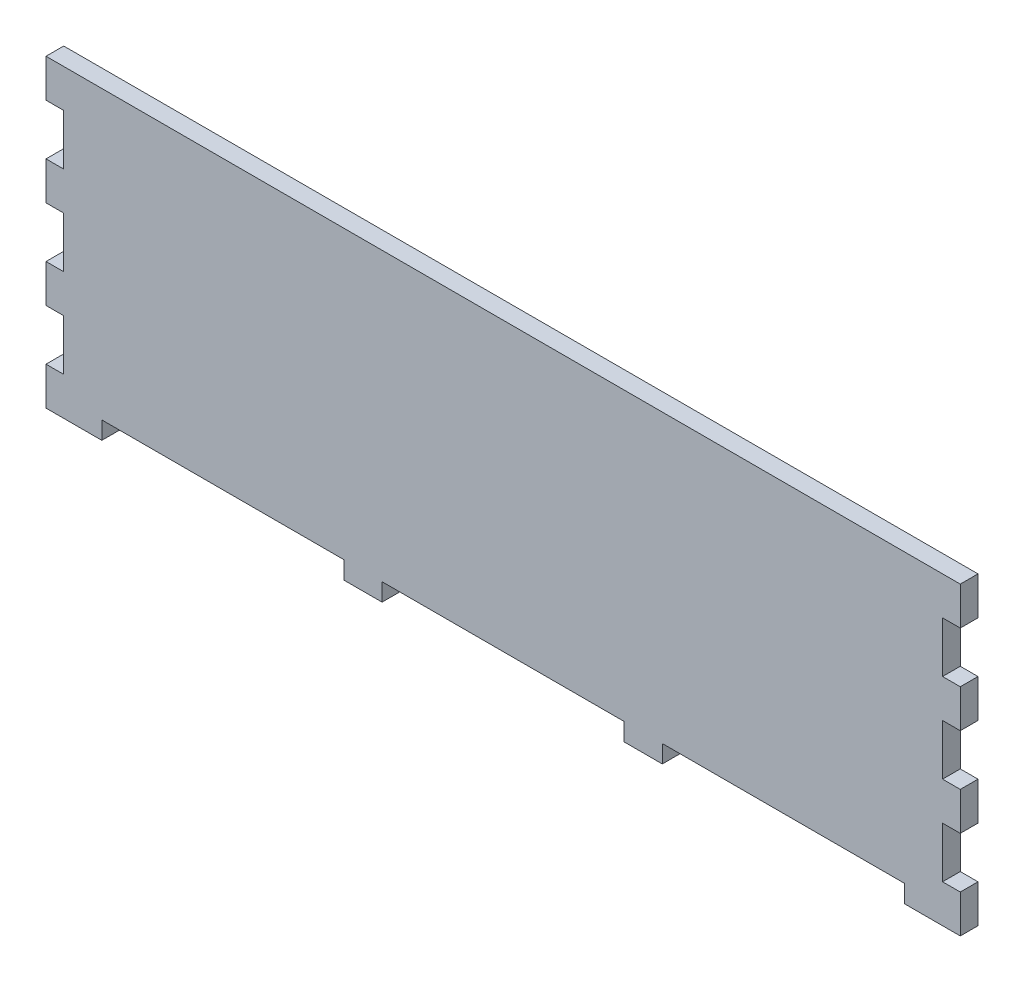
SolidWorks part; units mm, degrees
material "Oak"
ref_plane "Front Plane" through (0, 0, 0) normal (0, 0, 1) x (1, 0, 0)
ref_plane "Top Plane" through (0, 0, 0) normal (0, 1, 0) x (1, 0, 0)
ref_plane "Right Plane" through (0, 0, 0) normal (1, 0, 0) x (0, 0, -1)
sketch "Base_Sketch" plane through (0, 0, 0) normal (0, 0, 1) x (1, 0, 0)
  line L0 (-304.8, 103.4649) -> (304.8, 103.4649) construction
  line L1 (-292.99, 91.6549) -> (292.99, 91.6549)
  line L2 (-292.99, 91.6549) -> (-292.99, -99.7351)
  line L3 (-292.99, -99.7351) -> (292.99, -99.7351)
  line L4 (292.99, 91.6549) -> (292.99, -99.7351)
  line L5 (-292.99, 91.6549) -> (292.99, -99.7351) construction
  line L6 (-292.99, -99.7351) -> (292.99, 91.6549) construction
  line L7 (304.8, 103.4649) -> (304.8, -111.5451) construction
  line L8 (-304.8, -111.5451) -> (304.8, -111.5451) construction
  line L9 (-304.8, 103.4649) -> (-304.8, -111.5451) construction
  dimension "D1" = 11.81
extrude "Boss-Extrude1" add sketch "Base_Sketch" along normal blind 11.81
sketch "Joint_X" plane through (0, 0, 11.81) normal (0, 0, 1) x (1, 0, 0)
  line L1 (-292.99, -111.5451) -> (-267.59, -111.5451)
  line L2 (-292.99, -111.5451) -> (-292.99, -99.7351)
  line L3 (-292.99, -99.7351) -> (-267.59, -99.7351)
  line L4 (-267.59, -111.5451) -> (-267.59, -99.7351)
  point P5 (-267.59, -105.6401)
  dimension "D1" = 11.81
  dimension "D2" = 25.4
sketch "Joint_Y" plane through (0, 0, 11.81) normal (0, 0, 1) x (1, 0, 0)
  line L1 (-304.8, -111.5451) -> (-292.99, -111.5451)
  line L2 (-304.8, -111.5451) -> (-304.8, -86.1451)
  line L3 (-304.8, -86.1451) -> (-292.99, -86.1451)
  line L4 (-292.99, -111.5451) -> (-292.99, -86.1451)
  dimension "D1" = 11.81
  dimension "D2" = 25.4
extrude "Boss-Extrude2" add sketch "Joint_X" against normal blind 11.81
pattern_linear "LPattern1" count 4 spacing 186.86 along (1, 0, 0) of "Boss-Extrude2"
ref_plane "Plane1" through (0, 0, 0) normal (-1, 0, 0) x (0, 0, 1)
extrude "Boss-Extrude3" add sketch "Joint_Y" against normal blind 11.81
pattern_linear "LPattern2" count 4 spacing 59.2667 along (0, 1, 0) of "Boss-Extrude3"
mirror "Mirror3" about plane through (0, 0, 0) normal (-1, 0, 0) of "Boss-Extrude3", "LPattern2"
equation "\"Material_Thickness\"= \"Material_Thickness@Petrov.Assembly\""
equation "\"D1@Boss-Extrude1\"=\"Material_Thickness\""
equation "\"D1@Joint_X\" = \"Material_Thickness\""
equation "\"D1@Joint_Y\" = \"Material_Thickness\""
equation "\"D1@Boss-Extrude2\"=\"Material_Thickness\""
equation "\"D1@Boss-Extrude3\"=\"Material_Thickness\""
equation "\"Num_Joints\"= \"Num_Joints@Petrov.Assembly\""
equation "\"D1@LPattern2\"=\"Num_Joints\""
equation "\"D1@LPattern1\"=\"Num_Joints\""
equation "\"D1@Base_Sketch\"=\"Material_Thickness\""
equation "\"Joint_Size\"= \"Joint_Size@Petrov.Assembly\""
equation "\"D2@Joint_X\"=\"Joint_Size\""
equation "\"D2@Joint_Y\"=\"Joint_Size\""
